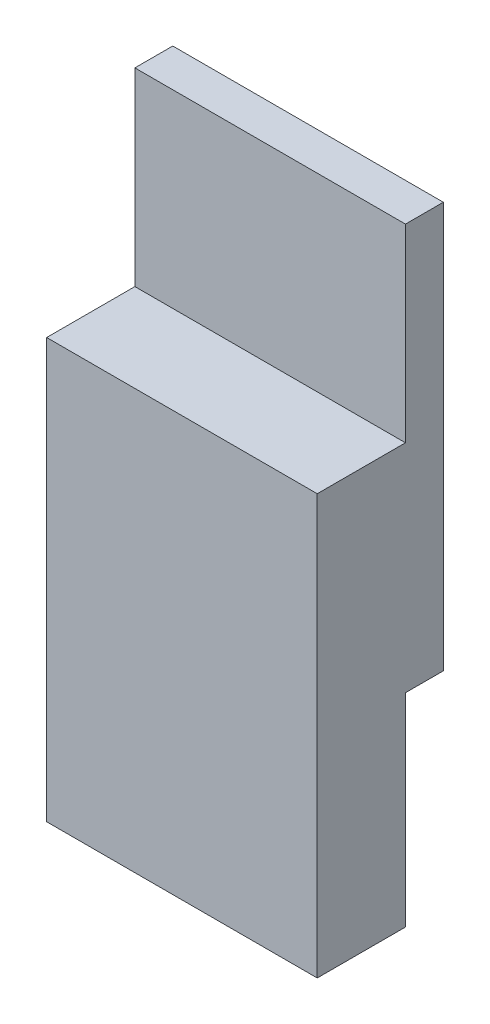
SolidWorks part; units mm, degrees
ref_plane "Ebene vorne" through (0, 0, 0) normal (0, 0, 1) x (1, 0, 0)
ref_plane "Ebene oben" through (0, 0, 0) normal (0, 1, 0) x (1, 0, 0)
ref_plane "Ebene rechts" through (0, 0, 0) normal (1, 0, 0) x (0, 0, -1)
sketch "Sketch1" plane through (0, 0, 0) normal (0, 0, 1) x (1, 0, 0)
  line L1 (-10, 7.5) -> (0, 7.5)
  line L2 (-10, 7.5) -> (-10, -7.5)
  line L3 (-10, -7.5) -> (0, -7.5)
  line L4 (0, 7.5) -> (0, -7.5)
  point P4 (0, 0)
  dimension "D1" = 10
  dimension "D2" = 15
extrude "Boss-Extrude1" add sketch "Sketch1" along normal blind 1.4 contours L3 L4 L1 L2
sketch "Sketch2" plane through (0, 0, 1.4) normal (0, 0, 1) x (1, 0, 0)
  line L0 (-10, 7.5) -> (-10, -7.5) construction
  line L1 (-10, 0.5) -> (0, 0.5)
  line L2 (-10, 0.5) -> (-10, -15)
  line L3 (-10, -15) -> (0, -15)
  line L4 (0, 0.5) -> (0, -15)
  line L5 (-10, 7.5) -> (0, 7.5) construction
  dimension "D1" = 22.5
  dimension "D2" = 7
extrude "Boss-Extrude2" add sketch "Sketch2" along normal blind 3.26
